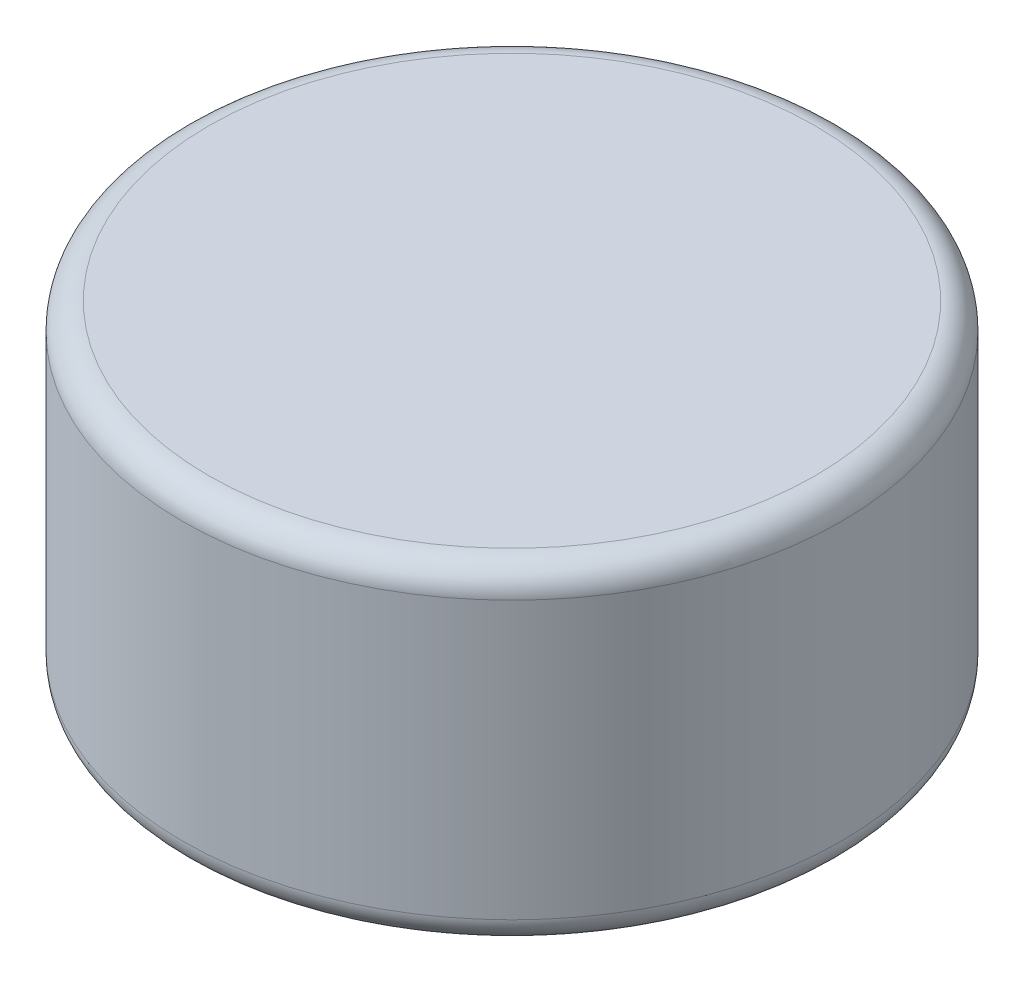
SolidWorks part; units mm, degrees
material "Ductile Iron"
ref_plane "Front" through (0, 0, 0) normal (0, 0, 1) x (1, 0, 0)
ref_plane "Top" through (0, 0, 0) normal (0, 1, 0) x (1, 0, 0)
ref_plane "Right" through (0, 0, 0) normal (1, 0, 0) x (0, 0, -1)
sketch "Sketch1" plane through (0, 0, 0) normal (0, 1, 0) x (1, 0, 0)
  circle A0 centre (0, 0) radius 3.175
  dimension "D1" = 6.35
extrude "Boss-Extrude1" add sketch "Sketch1" along normal blind 3.175
fillet "Fillet1" radius 0.254 2 edges at (0, 0, 3.175) (0, 3.175, 3.175)
